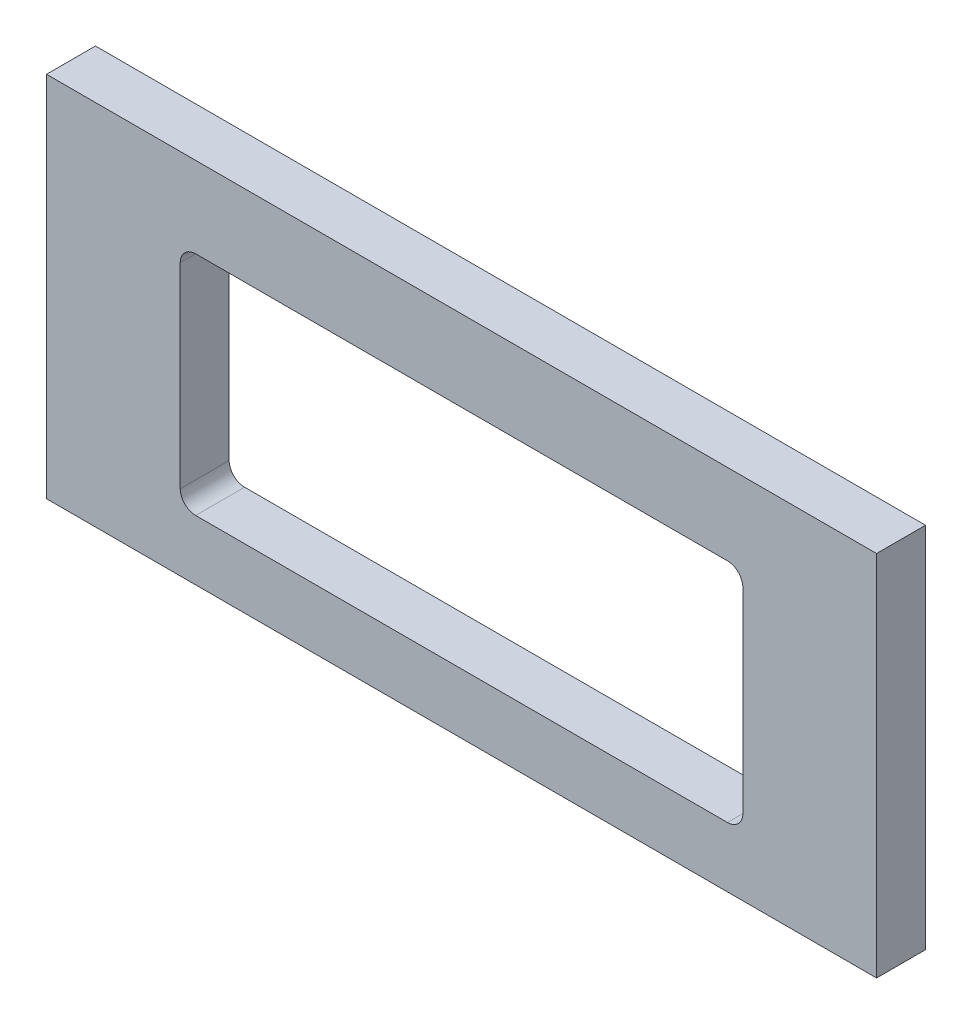
SolidWorks part; units mm, degrees
material "Acrylic (Medium-high impact)"
ref_plane "Front Plane" through (0, 0, 0) normal (0, 0, 1) x (1, 0, 0)
ref_plane "Top Plane" through (0, 0, 0) normal (0, 1, 0) x (1, 0, 0)
ref_plane "Right Plane" through (0, 0, 0) normal (1, 0, 0) x (0, 0, -1)
sketch "Sketch1" plane through (0, 0, 0) normal (0, 0, 1) x (1, 0, 0)
  line L0 (35.5, 9.8) -> (35.5, 35.2) construction
  line L1 (53.85, 0) -> (-53.85, 0)
  line L2 (53.85, 0) -> (53.85, 47.7)
  line L3 (53.85, 47.7) -> (-53.85, 47.7)
  line L4 (-53.85, 0) -> (-53.85, 47.7)
  line L5 (35.5, 8.8) -> (-35.5, 8.8) construction
  line L6 (35.5, 8.8) -> (35.5, 36.2) construction
  line L7 (35.5, 36.2) -> (-35.5, 36.2) construction
  line L8 (-35.5, 8.8) -> (-35.5, 36.2) construction
  line L9 (-34.5, 8.8) -> (34.5, 8.8) construction
  line L10 (-35.5, 35.2) -> (-35.5, 9.8) construction
  line L11 (34.5, 36.2) -> (-34.5, 36.2) construction
  line L12 (26.1277, 7.8) -> (26.1277, 8.8) construction
  line L13 (34.5, 7.8) -> (-34.5, 7.8)
  line L14 (36.5, 9.8) -> (36.5, 35.2)
  line L15 (34.5, 37.2) -> (-34.5, 37.2)
  line L16 (-36.5, 9.8) -> (-36.5, 35.2)
  line L17 (35.5, 20.8647) -> (36.5, 20.8647) construction
  line L18 (-36.5, 23.855) -> (-35.5, 23.855) construction
  line L19 (1.2688, 36.2) -> (1.2688, 37.2) construction
  arc A0 (-34.5, 7.8) -> (-36.5, 9.8) centre (-34.5, 9.8) cw
  arc A1 (-36.5, 35.2) -> (-34.5, 37.2) centre (-34.5, 35.2) cw
  arc A2 (34.5, 37.2) -> (36.5, 35.2) centre (34.5, 35.2) cw
  arc A3 (34.5, 7.8) -> (36.5, 9.8) centre (34.5, 9.8) ccw
  point P14 (33.69, 8.8)
  point P16 (-35.5, 18.0312)
  point P19 (30.3451, 36.2)
  dimension "D2" = 2
  dimension "D1" = 1
extrude "Boss-Extrude1" add sketch "Sketch1" along normal blind 6.35 contours L13 A3 L14 A2 L15 A1 L16 A0 | L2 L1 L4 L3
